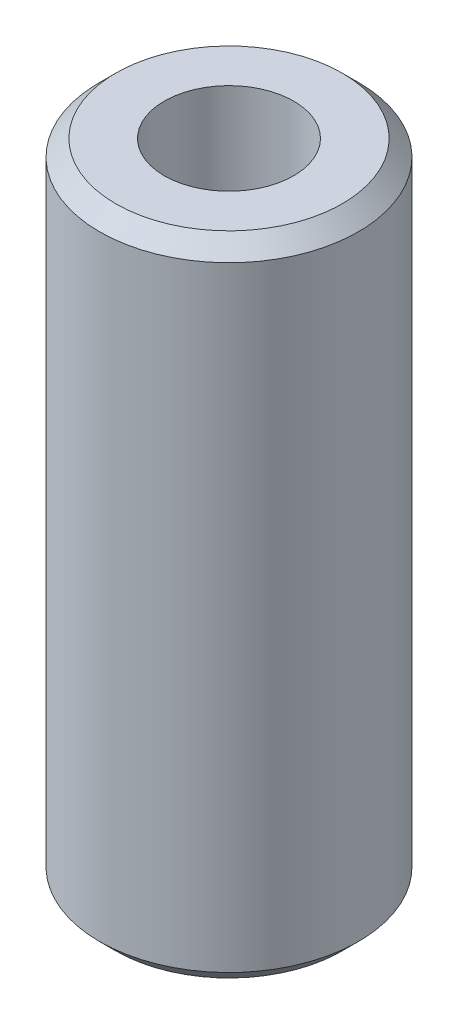
SolidWorks part; units mm, degrees
ref_plane "Front Plane" through (0, 0, 0) normal (0, 0, 1) x (1, 0, 0)
ref_plane "Top Plane" through (0, 0, 0) normal (0, 1, 0) x (1, 0, 0)
ref_plane "Right Plane" through (0, 0, 0) normal (1, 0, 0) x (0, 0, -1)
sketch "Sketch1" plane through (0, 0, 0) normal (0, 1, 0) x (1, 0, 0)
  circle A1 centre (0, 0) radius 2
  circle A2 centre (0, 0) radius 4
  dimension "D1" = 4
  dimension "D2" = 2
extrude "Boss-Extrude1" add sketch "Sketch1" along normal blind 20
chamfer "Chamfer1" distance 0.5 angle 45 2 edges at (0, 0, 4) (0, 20, 4)
